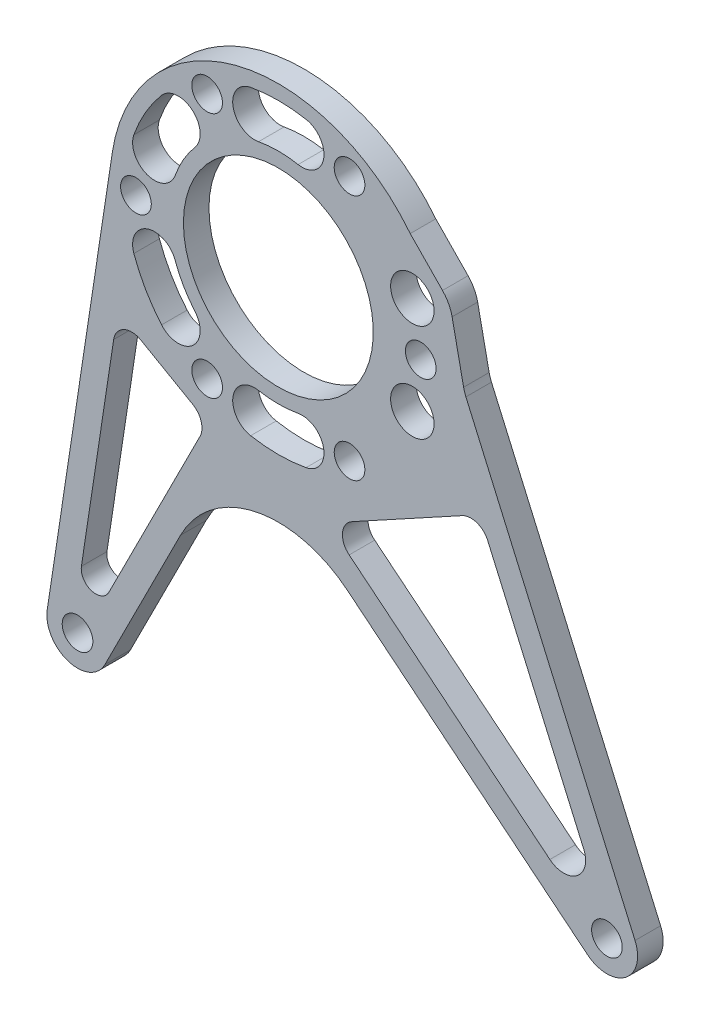
SolidWorks part; units mm, degrees
material "7075-T6 (SN)"
ref_plane "Front Plane" through (0, 0, 0) normal (0, 0, 1) x (1, 0, 0)
ref_plane "Top Plane" through (0, 0, 0) normal (0, 1, 0) x (1, 0, 0)
ref_plane "Right Plane" through (0, 0, 0) normal (1, 0, 0) x (0, 0, -1)
sketch "Sketch2" plane through (0, 0, 0) normal (0, 0, 1) x (1, 0, 0)
  line L3 (-45.4789, 6.9043) -> (-63.3048, -110.5156)
  line L4 (-47.5008, -115.5608) -> (-26.7828, -74.5065)
  line L5 (42.1363, 18.4535) -> (97.6945, -108.4066)
  line L6 (18.9404, -64.7574) -> (84.6967, -118.2906)
  line L7 (-55, -111.7764) -> (90, -111.7764) construction
  line L8 (0, 0) -> (0, -189.7871) construction
  line L9 (0, -114) -> (0, -494.7441) construction
  line L11 (0, 0) -> (89.3471, 0) construction
  line L12 (0, 0) -> (0, 84.554) construction
  circle A0 centre (0, 0) radius 26
  arc A1 (42.1363, 18.4535) -> (-45.4789, 6.9043) centre (0, 0) ccw
  arc A2 (-47.5008, -115.5608) -> (-63.3048, -110.5156) centre (-55, -111.7764) cw
  arc A3 (97.6945, -108.4066) -> (84.6967, -118.2906) centre (90, -111.7764) cw
  arc A4 (-26.7828, -74.5065) -> (18.9404, -64.7574) centre (0, -88.0224) cw
  circle A5 centre (-55, -111.7764) radius 4.2
  circle A6 centre (90, -111.7764) radius 4.2
  circle A7 centre (-39, 0) radius 4.2
  circle A8 centre (-19.5, 33.775) radius 4.2
  circle A9 centre (19.5, 33.775) radius 4.2
  circle A10 centre (39, 0) radius 4.2
  circle A11 centre (19.5, -33.775) radius 4.2
  circle A12 centre (-19.5, -33.775) radius 4.2
  circle A13 centre (36.7, 13.4) radius 5.95
  circle A14 centre (36.7, -13.4) radius 5.95
  point P39 (0, 0)
  dimension "D1" = 52
  dimension "D2" = 92
  dimension "D3" = 8.4
  dimension "D5" = 8.4
  dimension "D6" = 30
  dimension "D9" = 8.4
  dimension "D10" = 8.4
  dimension "D14" = 11.9
  dimension "D7" = 55
  dimension "D8" = 90
  dimension "D11" = 39
  dimension "D13" = 36.7
  dimension "D15" = 13.4
  dimension "D16" = 13.4
  dimension "D17" = 36.7
  dimension "D12" = 6
extrude "Boss-Extrude1" add sketch "Sketch2" against normal mid plane 7 contours L3 A2 L4 A4 L6 A3 L5 A1
sketch "Sketch4" plane through (0, 0, 3.5) normal (0, 0, 1) x (1, 0, 0)
  line L0 (29.3934, 35.384) -> (44.9636, 19.4098)
  line L2 (47.5928, 14.4674) -> (50.7407, -0.6583)
  line L3 (42.1363, 18.4535) -> (97.6945, -108.4066) construction
  line L8 (-45.4789, 6.9043) -> (-63.3048, -110.5156)
  line L9 (-47.5008, -115.5608) -> (-26.7828, -74.5065)
  line L10 (18.9404, -64.7574) -> (84.6967, -118.2906)
  line L11 (97.6945, -108.4066) -> (42.1363, 18.4535)
  line L12 (-45.4789, 6.9043) -> (-63.3048, -110.5156)
  line L13 (-47.5008, -115.5608) -> (-26.7828, -74.5065)
  line L14 (18.9404, -64.7574) -> (84.6967, -118.2906)
  line L15 (97.6945, -108.4066) -> (51.3708, -2.6324)
  arc A0 (42.1363, 18.4535) -> (-45.4789, 6.9043) centre (0, 0) ccw construction
  arc A1 (50.7407, -0.6583) -> (51.3708, -2.6324) centre (60.5309, 1.3793) ccw
  arc A2 (44.9636, 19.4098) -> (47.5928, 14.4674) centre (37.8025, 12.4298) cw
  arc A5 (42.1363, 18.4535) -> (-45.4789, 6.9043) centre (0, 0) ccw
  arc A6 (-63.3048, -110.5156) -> (-47.5008, -115.5608) centre (-55, -111.7764) ccw
  arc A7 (18.9404, -64.7574) -> (-26.7828, -74.5065) centre (0, -88.0224) ccw
  arc A8 (84.6967, -118.2906) -> (97.6945, -108.4066) centre (90, -111.7764) ccw
  arc A9 (29.3934, 35.384) -> (-45.4789, 6.9043) centre (0, 0) ccw
  arc A10 (-63.3048, -110.5156) -> (-47.5008, -115.5608) centre (-55, -111.7764) ccw
  arc A11 (18.9404, -64.7574) -> (-26.7828, -74.5065) centre (0, -88.0224) ccw
  arc A12 (84.6967, -118.2906) -> (97.6945, -108.4066) centre (90, -111.7764) ccw
  point P17 (50.9529, -1.6781)
  point P30 (46.9987, 17.3219)
  dimension "D5" = 10
  dimension "D1" = 4
  dimension "D2" = 25.2228
  dimension "D3" = 19
  dimension "D4" = 0
extrude "Boss-Extrude4" add sketch "Sketch4" against normal through all
sketch "Sketch3" plane through (0, 0, -3.5) normal (0, 0, -1) x (-1, 0, 0)
  circle A0 centre (0, 0) radius 26
  circle A1 centre (19.5, 33.775) radius 4.2
  circle A2 centre (-19.5, 33.775) radius 4.2
  circle A3 centre (-36.7, 13.4) radius 5.95
  circle A4 centre (-39, 0) radius 4.2
  circle A5 centre (-36.7, -13.4) radius 5.95
  circle A6 centre (-19.5, -33.775) radius 4.2
  circle A7 centre (19.5, -33.775) radius 4.2
  circle A8 centre (39, 0) radius 4.2
  circle A9 centre (-90, -111.7764) radius 4.2
  circle A10 centre (55, -111.7764) radius 4.2
extrude "Cut-Extrude1" cut sketch "Sketch3" against normal through all
sketch "Sketch5" plane through (0, 0, -3.5) normal (0, 0, -1) x (-1, 0, 0)
  line L6 (-50.3501, -31.3095) -> (-20.1503, -47.8365)
  line L7 (-19.3939, -56.1002) -> (-74.3704, -100.8574)
  line L8 (-83.6545, -93.7974) -> (-57.3305, -33.6898)
  line L9 (-42.1363, 18.4535) -> (-97.6945, -108.4066) construction
  line L10 (-18.9404, -64.7574) -> (-84.6967, -118.2906) construction
  arc A3 (-74.3704, -100.8574) -> (-83.6545, -93.7974) centre (-78.1585, -96.2044) cw
  arc A4 (-20.1503, -47.8365) -> (-19.3939, -56.1002) centre (-22.5507, -52.2227) cw
  arc A5 (-50.3501, -31.3095) -> (-57.3305, -33.6898) centre (-52.7505, -35.6956) ccw
  dimension "D1" = 7
  dimension "D2" = 7
  dimension "D3" = 6
  dimension "D4" = 5
extrude "Cut-Extrude3" cut sketch "Sketch5" against normal through all contours A5 L8 A3 L7 A4 L6
sketch "Sketch7" plane through (0, 0, -3.5) normal (0, 0, -1) x (-1, 0, 0)
  line L0 (23.4334, -41.8134) -> (37.6768, -33.666)
  line L1 (45.1028, -37.2557) -> (53.9403, -95.4686)
  line L2 (46.4146, -97.8711) -> (21.4522, -48.4062)
  line L3 (47.5008, -115.5608) -> (26.7828, -74.5065) construction
  line L4 (45.4789, 6.9043) -> (63.3048, -110.5156) construction
  arc A0 (37.6768, -33.666) -> (45.1028, -37.2557) centre (40.1594, -38.0061) cw
  arc A1 (23.4334, -41.8134) -> (21.4522, -48.4062) centre (25.916, -46.1535) ccw
  arc A2 (53.9403, -95.4686) -> (46.4146, -97.8711) centre (49.9856, -96.069) cw
  dimension "D3" = 5
  dimension "D4" = 4
  dimension "D1" = 7
  dimension "D2" = 7
extrude "Cut-Extrude5" cut sketch "Sketch7" against normal through all
sketch "Sketch8" plane through (0, 0, -3.5) normal (0, 0, -1) x (-1, 0, 0)
  line L0 (0, 0) -> (0, 84.554) construction
  arc A0 (-6.5, 35.4083) -> (6.5, 35.4083) centre (0, 0) cw construction
  arc A1 (7.5833, 41.3097) -> (-7.5833, 41.3097) centre (0, 0) ccw
  arc A2 (5.4167, 29.5069) -> (-5.4167, 29.5069) centre (0, 0) ccw
  arc A3 (5.4167, 29.5069) -> (7.5833, 41.3097) centre (6.5, 35.4083) ccw
  arc A4 (-7.5833, 41.3097) -> (-5.4167, 29.5069) centre (-6.5, 35.4083) ccw
  circle A5 centre (0, 0) radius 26 construction
  arc A6 (45.4789, 6.9043) -> (-42.1363, 18.4535) centre (0, 0) ccw construction
  point P4 (0, 36)
  dimension "D1" = 4
  dimension "D2" = 4
  dimension "D3" = 13
extrude "Cut-Extrude6" cut sketch "Sketch8" against normal through all
ref_axis "Axis1" through (0, 0, 37.0505) along (0, 0, -1)
pattern_circular "CirPattern1" count 6 over 360 about axis through (0, 0, 37.0505) along (0, 0, -1) skipping 1, 2 of "Cut-Extrude6"
